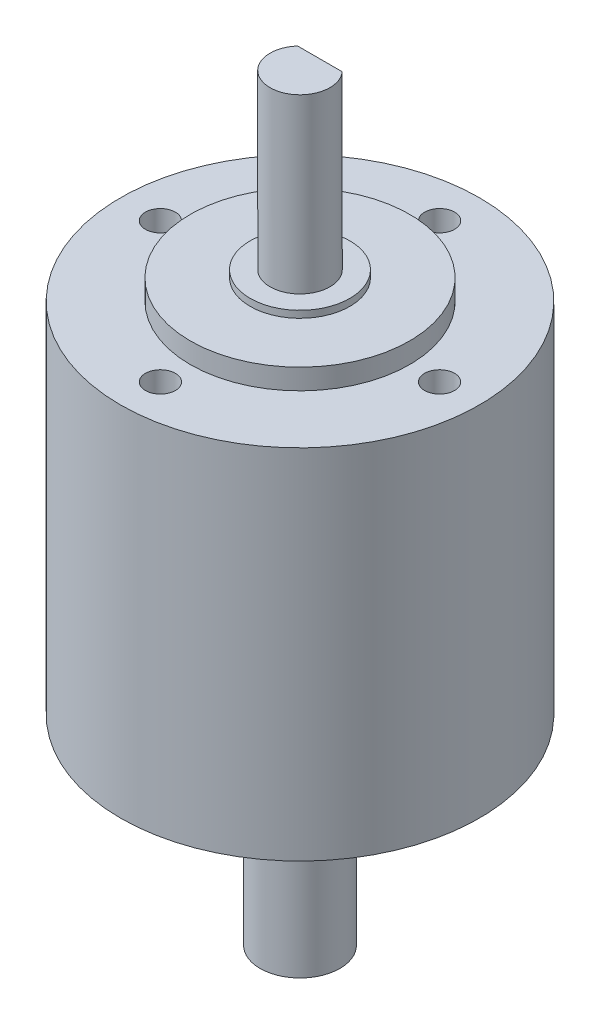
SolidWorks part; units mm, degrees
ref_plane "Front Plane" through (0, 0, 0) normal (0, 0, 1) x (1, 0, 0)
ref_plane "Top Plane" through (0, 0, 0) normal (0, 1, 0) x (1, 0, 0)
ref_plane "Right Plane" through (0, 0, 0) normal (1, 0, 0) x (0, 0, -1)
sketch "Sketch1" plane through (0, 0, 0) normal (0, 1, 0) x (1, 0, 0)
  circle A0 centre (0, 0) radius 18
  dimension "D1" = 36
extrude "Boss-Extrude1" add sketch "Sketch1" along normal mid plane 35.8902
sketch "Sketch2" plane through (0, 17.9451, 0) normal (0, 1, 0) x (1, 0, 0)
  circle A0 centre (0, 0) radius 11
  dimension "D1" = 22
extrude "Boss-Extrude2" add sketch "Sketch2" along normal mid plane 40.005 from surface at -17.9451 starting at plane "Top Plane"
sketch "Sketch3" plane through (0, 20.0025, 0) normal (0, 1, 0) x (1, 0, 0)
  circle A0 centre (0, 0) radius 3
  dimension "D1" = 6
extrude "Boss-Extrude4" add sketch "Sketch3" along normal blind 18
sketch "Sketch4" plane through (0, 38.0025, 0) normal (0, 1, 0) x (1, 0, 0)
  line L0 (-2.2361, 2) -> (2.2361, 2)
  line L1 (0, -3) -> (0, 2) construction
  arc A0 (0, -3) -> (2.2361, 2) centre (0, 0) ccw construction
  circle A1 centre (0, 0) radius 3
  arc A2 (2.2361, 2) -> (-2.2361, 2) centre (0, 0) ccw
  arc A3 (-2.2361, 2) -> (0, -3) centre (0, 0) ccw construction
  dimension "D2" = 5
  dimension "D1" = 0
extrude "Cut-Extrude1" cut sketch "Sketch4" against normal blind 15
sketch "Sketch5" plane through (0, 17.9451, 0) normal (0, 1, 0) x (1, 0, 0)
  circle A0 centre (0, 0) radius 14 construction
  circle A1 centre (0, 14) radius 1.5
  circle A2 centre (-14, 0) radius 1.5
  circle A3 centre (0, -14) radius 1.5
  circle A4 centre (14, 0) radius 1.5
  dimension "D1" = 28
  dimension "D2" = 3
extrude "Cut-Extrude2" cut sketch "Sketch5" against normal blind 4
mirror "Mirror1" about plane through (0, 0, 0) normal (0, 1, 0) of "Cut-Extrude2", "Cut-Extrude1"
sketch "Sketch6" plane through (0, -20.0025, 0) normal (0, -1, 0) x (1, 0, 0)
  circle A0 centre (0, 0) radius 4
  dimension "D1" = 8
extrude "Boss-Extrude5" add sketch "Sketch6" along normal blind 18
sketch "Sketch7" plane through (0, -38.0025, 0) normal (0, -1, 0) x (1, 0, 0)
  line L0 (-2.6458, -3) -> (2.6458, -3)
  line L1 (0, -3) -> (0, -4) construction
  arc A0 (2.6458, -3) -> (-2.6458, -3) centre (0, 0) cw
  circle A2 centre (0, 0) radius 4 construction
  point P4 (2.6807, -2.9688)
  dimension "D1" = 1
extrude "Cut-Extrude3" cut sketch "Sketch7" against normal offset from surface (15 mm away) 3 up to face at (0, -20.0025, -4)
sketch "Sketch9" plane through (0, 0, 0) normal (0, 1, 0) x (1, 0, 0)
  circle A0 centre (0, 0) radius 5
  dimension "D1" = 10
extrude "Boss-Extrude6" add sketch "Sketch9" along normal mid plane 41.402
